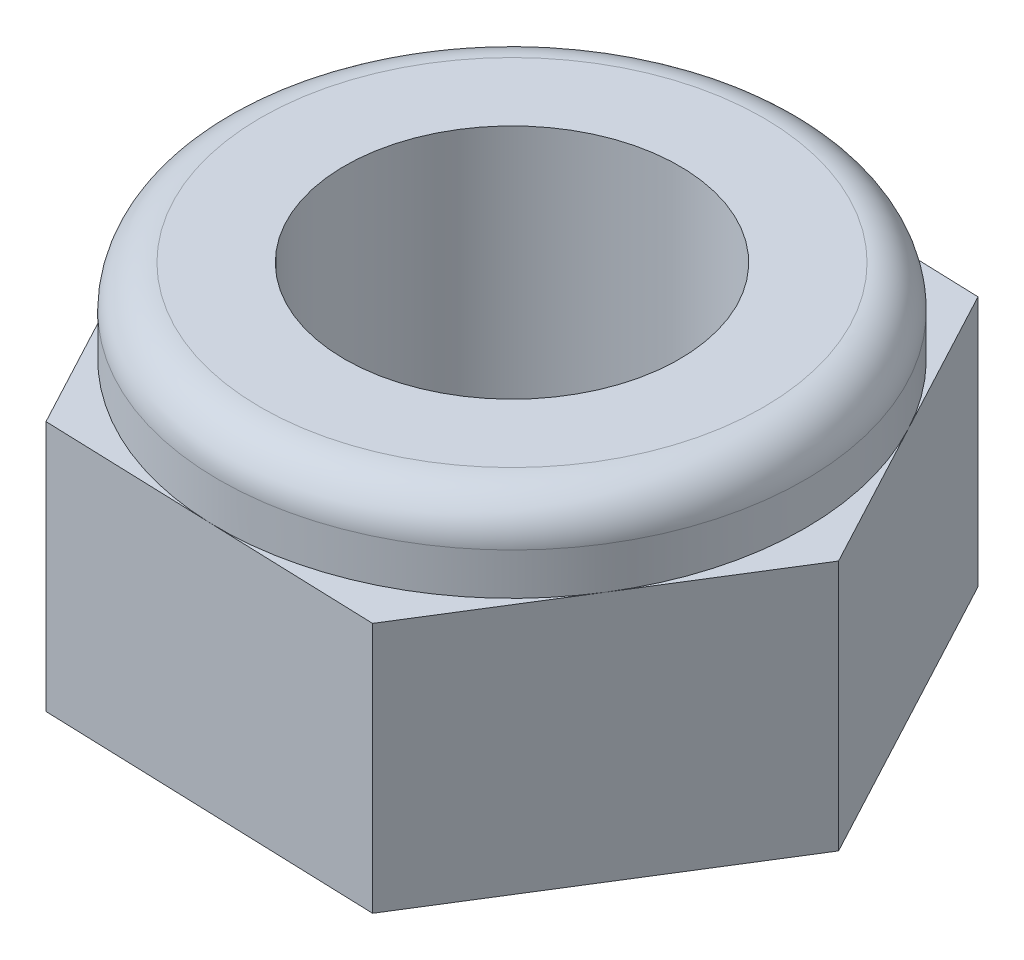
SolidWorks part; units mm, degrees
ref_plane "前视基准面" through (0, 0, 0) normal (0, 0, 1) x (1, 0, 0)
ref_plane "上视基准面" through (0, 0, 0) normal (0, 1, 0) x (1, 0, 0)
ref_plane "右视基准面" through (0, 0, 0) normal (1, 0, 0) x (0, 0, -1)
sketch "草图1" plane through (0, 0, 0) normal (0, 1, 0) x (1, 0, 0)
  line L1 (2.1384, 3.4294) -> (-1.9007, 3.5666)
  line L2 (-1.9007, 3.5666) -> (-4.0391, 0.1372)
  line L3 (-4.0391, 0.1372) -> (-2.1384, -3.4294)
  line L4 (-2.1384, -3.4294) -> (1.9007, -3.5666)
  line L5 (1.9007, -3.5666) -> (4.0391, -0.1372)
  line L6 (4.0391, -0.1372) -> (2.1384, 3.4294)
  circle A1 centre (0, 0) radius 3.5 construction
  dimension "D1" = 7
extrude "凸台-拉伸1" add sketch "草图1" along normal blind 3 contours L6 L1 L2 L3 L4 L5
sketch "草图2" plane through (0, 3, 0) normal (0, 1, 0) x (1, 0, 0)
  line L0 (2.1384, 3.4294) -> (-1.9007, 3.5666) construction
  circle A0 centre (0, 0) radius 3.5
extrude "凸台-拉伸2" add sketch "草图2" along normal blind 1
sketch "草图4" plane through (0, 4, 0) normal (0, 1, 0) x (1, 0, 0)
  circle A0 centre (0, 0) radius 2
  dimension "D1" = 4
extrude "切除-拉伸1" cut sketch "草图4" against normal through all
cosmetic thread "装饰螺纹线1" parameters "D2"=6
fillet "圆角1" radius 0.5 1 edges at (0, 4, 3.5)
